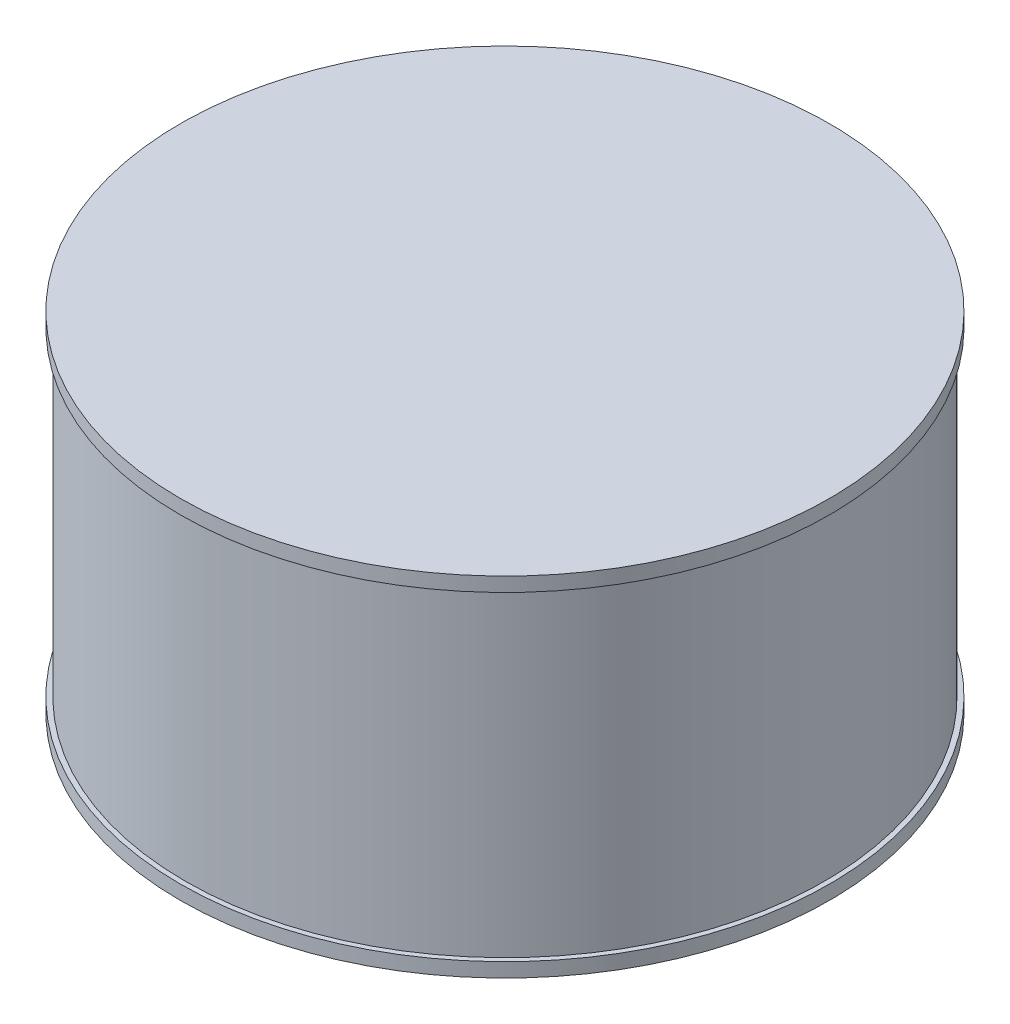
SolidWorks part; units mm, degrees
ref_plane "Front Plane" through (0, 0, 0) normal (0, 0, 1) x (1, 0, 0)
ref_plane "Top Plane" through (0, 0, 0) normal (0, 1, 0) x (1, 0, 0)
ref_plane "Right Plane" through (0, 0, 0) normal (1, 0, 0) x (0, 0, -1)
sketch "Sketch1" plane through (0, 0, 0) normal (0, 1, 0) x (1, 0, 0)
  circle A0 centre (0, 0) radius 45
  dimension "D1" = 90
extrude "Boss-Extrude1" add sketch "Sketch1" along normal mid plane 45
sketch "Sketch2" plane through (0, 22.5, 0) normal (0, 1, 0) x (1, 0, 0)
  circle A2 centre (0, 0) radius 45.69
  circle A3 centre (0, 0) radius 45.69
  dimension "D1" = 0.69
extrude "Boss-Extrude2" add sketch "Sketch2" along normal blind 2
mirror "Mirror1" about plane through (0, 0, 0) normal (0, 1, 0) of "Boss-Extrude2"
